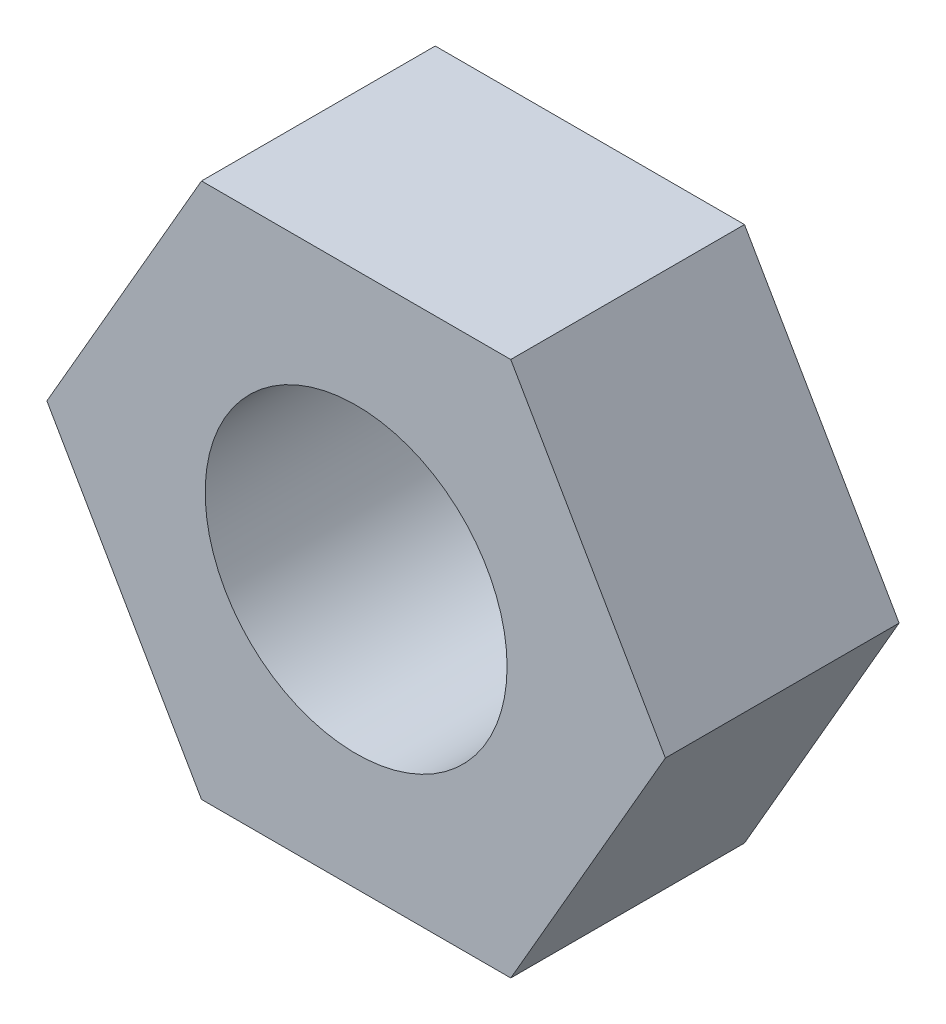
SolidWorks part; units mm, degrees
material "AISI 304"
ref_plane "前视基准面" through (0, 0, 0) normal (0, 0, 1) x (1, 0, 0)
ref_plane "上视基准面" through (0, 0, 0) normal (0, 1, 0) x (1, 0, 0)
ref_plane "右视基准面" through (0, 0, 0) normal (1, 0, 0) x (0, 0, -1)
other "Configuration Table"
sketch "草图1" plane through (0, 0, 0) normal (0, 0, 1) x (1, 0, 0)
  line L1 (3.1754, 0) -> (1.5877, 2.75)
  line L2 (1.5877, 2.75) -> (-1.5877, 2.75)
  line L3 (-1.5877, 2.75) -> (-3.1754, 0)
  line L4 (-3.1754, 0) -> (-1.5877, -2.75)
  line L5 (-1.5877, -2.75) -> (1.5877, -2.75)
  line L6 (1.5877, -2.75) -> (3.1754, 0)
  circle A0 centre (0, 0) radius 1.55
  circle A1 centre (0, 0) radius 2.75 construction
  dimension "D1" = 3.1
  dimension "D2" = 5.5
extrude "凸台-拉伸1" add sketch "草图1" along normal blind 2.4
